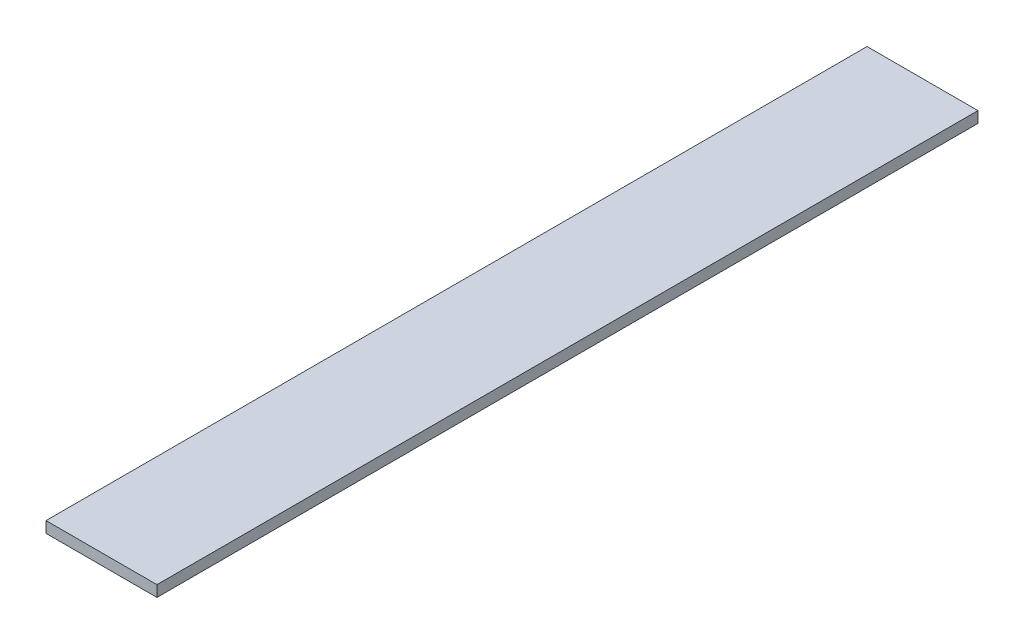
SolidWorks part; units mm, degrees
ref_plane "Front Plane" through (0, 0, 0) normal (0, 0, 1) x (1, 0, 0)
ref_plane "Top Plane" through (0, 0, 0) normal (0, 1, 0) x (1, 0, 0)
ref_plane "Right Plane" through (0, 0, 0) normal (1, 0, 0) x (0, 0, -1)
sketch "Sketch1" plane through (0, 0, 0) normal (0, 1, 0) x (1, 0, 0)
  line L1 (0, 0) -> (63.5, 0)
  line L2 (0, 0) -> (0, 469.9)
  line L3 (0, 469.9) -> (63.5, 469.9)
  line L4 (63.5, 0) -> (63.5, 469.9)
  dimension "D1" = 63.5
  dimension "D2" = 469.9
extrude "Boss-Extrude1" add sketch "Sketch1" along normal blind 6.35
ref_plane "Plane1" through (0, 0, -234.95) normal (0, 0, -1) x (-1, 0, 0)
ref_plane "Plane2" through (31.75, 0, 0) normal (1, 0, 0) x (0, 0, -1)
